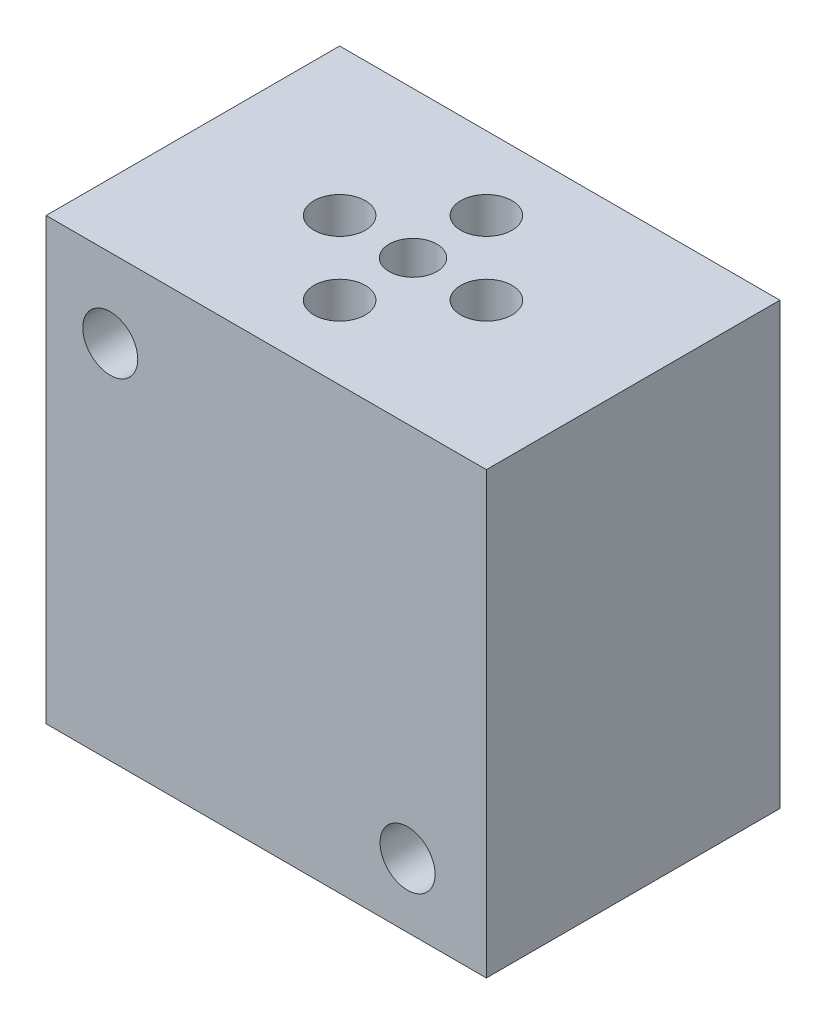
SolidWorks part; units mm, degrees
ref_plane "Front Plane" through (0, 0, 0) normal (0, 0, 1) x (1, 0, 0)
ref_plane "Top Plane" through (0, 0, 0) normal (0, 1, 0) x (1, 0, 0)
ref_plane "Right Plane" through (0, 0, 0) normal (1, 0, 0) x (0, 0, -1)
sketch "Sketch3" plane through (0, 0, 0) normal (0, 1, 0) x (1, 0, 0)
  line L1 (-40.3412, 23.5946) -> (35.8588, 23.5946)
  line L2 (-40.3412, 23.5946) -> (-40.3412, -27.2054)
  line L3 (-40.3412, -27.2054) -> (35.8588, -27.2054)
  line L4 (35.8588, 23.5946) -> (35.8588, -27.2054)
  dimension "D1" = 50.8
  dimension "D2" = 76.2
extrude "Boss-Extrude1" add sketch "Sketch3" along normal blind 76.2
sketch "Sketch5" plane through (0, 76.2, 0) normal (0, 1, 0) x (1, 0, 0)
  line L0 (-40.3412, 23.5946) -> (-40.3412, -27.2054) construction
  line L1 (-40.3412, -27.2054) -> (35.8588, -27.2054) construction
  circle A0 centre (-2.2412, -1.8054) radius 4.1275
  point P2 (0, 0)
  point P7 (0, 0)
  point P9 (-0.0533, -4.6861)
  dimension "D3" = 8.255
  dimension "D1" = 38.1
  dimension "D2" = 25.4
extrude "Cut-Extrude1" cut sketch "Sketch5" against normal blind 76.2
sketch "Sketch6" plane through (0, 76.2, 0) normal (0, 1, 0) x (1, 0, 0)
  line L0 (35.8588, 23.5946) -> (-40.3412, 23.5946) construction
  line L1 (-40.3412, 23.5946) -> (-40.3412, -27.2054) construction
  circle A0 centre (-14.9412, -1.8054) radius 4.445
  dimension "D1" = 8.89
  dimension "D2" = 25.4
  dimension "D3" = 25.4
extrude "Cut-Extrude2" cut sketch "Sketch6" against normal blind 76.2
sketch "Sketch8" plane through (0, 76.2, 0) normal (0, 1, 0) x (1, 0, 0)
  line L2 (-40.3412, -27.2054) -> (35.8588, -27.2054) construction
  line L3 (35.8588, -27.2054) -> (35.8588, 23.5946) construction
  circle A0 centre (10.4588, -1.8054) radius 4.445
  dimension "D1" = 8.89
  dimension "D2" = 25.4
  dimension "D3" = 25.4
extrude "Cut-Extrude4" cut sketch "Sketch8" against normal blind 76.2
sketch "Sketch9" plane through (0, 76.2, 0) normal (0, 1, 0) x (1, 0, 0)
  line L2 (-40.3412, -27.2054) -> (35.8588, -27.2054) construction
  line L3 (-40.3412, 23.5946) -> (-40.3412, -27.2054) construction
  circle A0 centre (-2.2412, -14.5054) radius 4.445
  dimension "D1" = 8.89
  dimension "D2" = 12.7
  dimension "D3" = 38.1
extrude "Cut-Extrude5" cut sketch "Sketch9" against normal blind 76.2
sketch "Sketch10" plane through (0, 76.2, 0) normal (0, 1, 0) x (1, 0, 0)
  line L2 (-40.3412, 23.5946) -> (-40.3412, -27.2054) construction
  line L3 (35.8588, 23.5946) -> (-40.3412, 23.5946) construction
  circle A0 centre (-2.2412, 10.8946) radius 4.445
  dimension "D1" = 8.89
  dimension "D2" = 38.1
  dimension "D3" = 12.7
extrude "Cut-Extrude6" cut sketch "Sketch10" against normal blind 76.2
sketch "Sketch12" plane through (0, 0, 27.2054) normal (0, 0, 1) x (1, 0, 0)
  line L0 (-40.3412, 76.2) -> (-40.3412, 0) construction
  line L1 (-40.3412, 76.2) -> (35.8588, 76.2) construction
  circle A0 centre (-29.2414, 62.5602) radius 4.7625
  dimension "D1" = 9.525
  dimension "D2" = 11.0998
  dimension "D3" = 13.6398
extrude "Cut-Extrude7" cut sketch "Sketch12" against normal blind 76.2
sketch "Sketch13" plane through (0, 0, 27.2054) normal (0, 0, 1) x (1, 0, 0)
  line L2 (-40.3412, 0) -> (35.8588, 0) construction
  line L3 (35.8588, 76.2) -> (35.8588, 0) construction
  circle A0 centre (22.219, 11.0998) radius 4.7625
  dimension "D1" = 9.525
  dimension "D2" = 11.0998
  dimension "D3" = 13.6398
extrude "Cut-Extrude8" cut sketch "Sketch13" against normal blind 76.2
